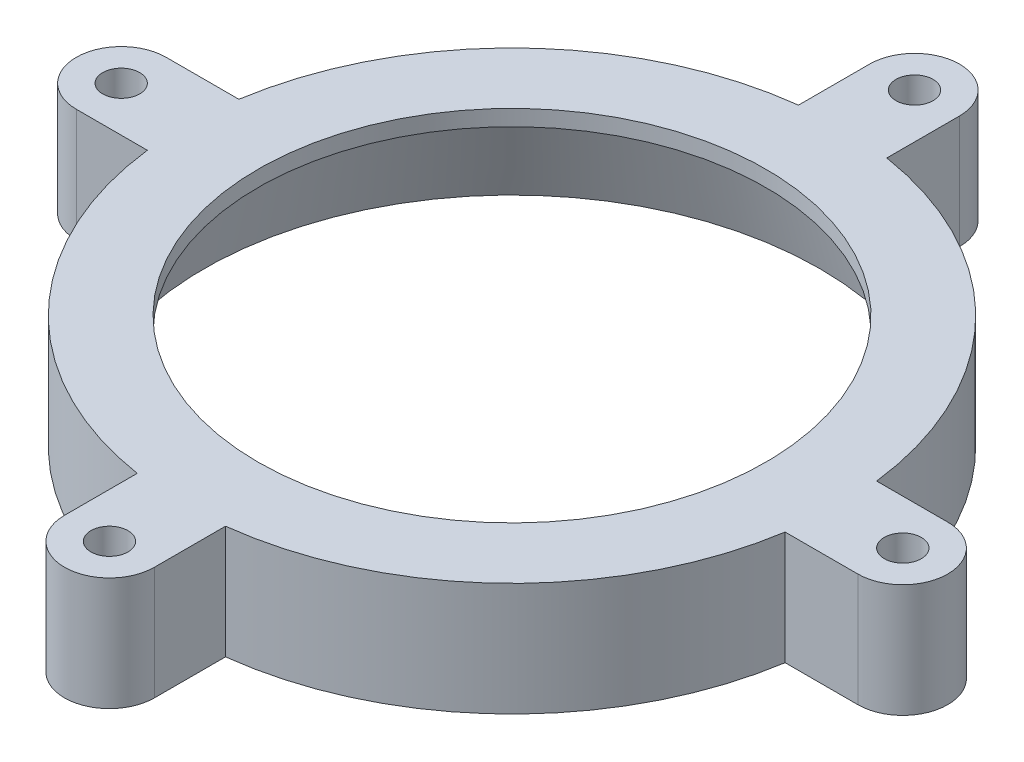
SolidWorks part; units mm, degrees
ref_plane "Front Plane" through (0, 0, 0) normal (0, 0, 1) x (1, 0, 0)
ref_plane "Top Plane" through (0, 0, 0) normal (0, 1, 0) x (1, 0, 0)
ref_plane "Right Plane" through (0, 0, 0) normal (1, 0, 0) x (0, 0, -1)
sketch "Sketch1" plane through (0, 0, 0) normal (0, 1, 0) x (1, 0, 0)
  circle A0 centre (0, 0) radius 58.2
  circle A1 centre (0, 0) radius 62
  dimension "D1" = 116.4
  dimension "D2" = 124
extrude "Boss-Extrude1" add sketch "Sketch1" along normal blind 18.4 draft 15 draft outward yes
sketch "Sketch2" plane through (0, 0, 0) normal (0, -1, 0) x (1, 0, 0)
  circle A0 centre (0, 0) radius 62
  circle A1 centre (0, 0) radius 82
  dimension "D1" = 20
extrude "Cut-Extrude1" cut sketch "Sketch2" against normal through all
sketch "Sketch3" plane through (0, 18.4, 0) normal (0, 1, 0) x (1, 0, 0)
  circle A0 centre (0, 0) radius 62
  circle A1 centre (0, 0) radius 48
  dimension "D1" = 96
  dimension "D2" = 124
extrude "Boss-Extrude2" add sketch "Sketch3" along normal blind 3
sketch "Sketch4" plane through (0, 21.4, 0) normal (0, 1, 0) x (1, 0, 0)
  line L0 (-75, 9.6103) -> (-58.4809, 9.6103)
  line L1 (-58.4809, 9.6103) -> (-58.4809, -7.3897)
  line L2 (-58.4809, -7.3897) -> (-75, -7.3897)
  arc A0 (-75, 9.6103) -> (-75, -7.3897) centre (-75, 1.1103) ccw
  circle A1 centre (-75, 1.1103) radius 2.125
  dimension "D1" = 17
  dimension "D3" = 4.25
  dimension "D2" = 75
extrude "Boss-Extrude3" add sketch "Sketch4" against normal up to surface (21.4 mm away) up to face at (0, 0, -62)
pattern_circular "CirPattern1" count 4 over 360 about axis through (0, 0, 0) along (0, 1, 0) of "Boss-Extrude3"
sketch "Sketch5" plane through (0, 21.4, 0) normal (0, 1, 0) x (1, 0, 0)
  circle A0 centre (-75, 1.1103) radius 3.5
  circle A1 centre (1.1103, 75) radius 3.5
  circle A2 centre (75, -1.1103) radius 3.5
  circle A3 centre (-1.1103, -75) radius 3.5
  point P12 (0, 0)
  dimension "D1" = 7
  dimension "D2" = 4
extrude "Cut-Extrude2" cut sketch "Sketch5" against normal blind 9.4
